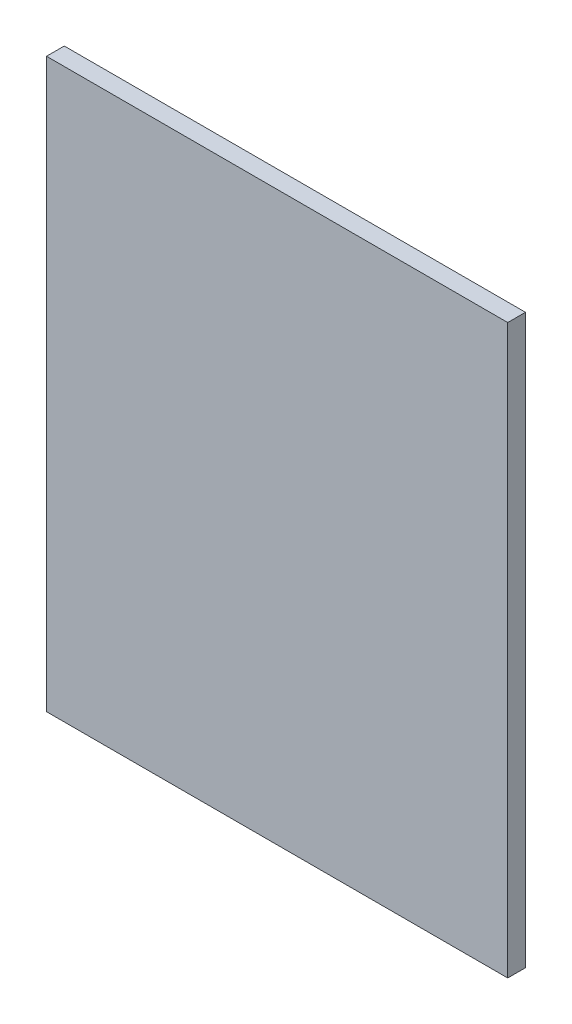
SolidWorks part; units mm, degrees
ref_plane "Front Plane" through (0, 0, 0) normal (0, 0, 1) x (1, 0, 0)
ref_plane "Top Plane" through (0, 0, 0) normal (0, 1, 0) x (1, 0, 0)
ref_plane "Right Plane" through (0, 0, 0) normal (1, 0, 0) x (0, 0, -1)
sketch "Sketch1" plane through (0, 0, 0) normal (0, 0, 1) x (1, 0, 0)
  line L0 (0, 0) -> (0, 160)
  line L1 (0, 160) -> (-130, 160)
  line L2 (-130, 160) -> (-130, 0)
  line L3 (-130, 0) -> (0, 0)
  dimension "D1" = 130
  dimension "D2" = 160
extrude "Boss-Extrude1" add sketch "Sketch1" along normal blind 5
